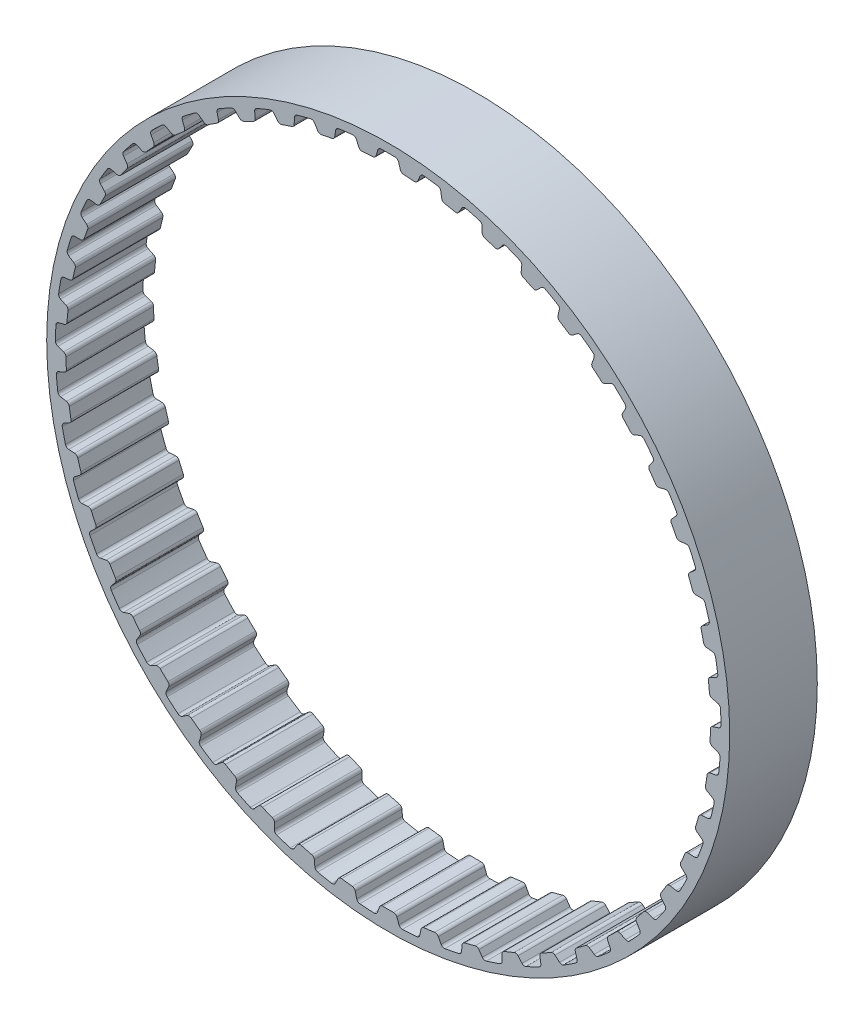
SolidWorks part; units mm, degrees
ref_plane "Front Plane" through (0, 0, 0) normal (0, 0, 1) x (1, 0, 0)
ref_plane "Top Plane" through (0, 0, 0) normal (0, 1, 0) x (1, 0, 0)
ref_plane "Right Plane" through (0, 0, 0) normal (1, 0, 0) x (0, 0, -1)
sketch "Sketch1" plane through (0, 0, 0) normal (0, 0, 1) x (1, 0, 0)
  line L0 (0, 0) -> (-2.3573, 36.7174) construction
  line L1 (0, 0) -> (2.3573, 36.7174) construction
  line L2 (2.3573, 36.7174) -> (-2.3573, 36.7174) construction
  line L3 (2.3573, 36.7174) -> (-2.3573, 36.7174) construction
  circle A0 centre (0, 0) radius 38.993
  circle A1 centre (0, 0) radius 36.793
  circle A2 centre (0, 0) radius 37.993 construction
  dimension "OD" = 77.986
  dimension "Angle Distance" = 7.347
  dimension "hs" = 2.2
  dimension "ht" = 1.2
extrude "Boss-Extrude1" add sketch "Sketch1" along normal mid plane 10
sketch "Sketch2" plane through (0, 0, 0) normal (0, 0, 1) x (1, 0, 0)
  line L1 (0, 38.993) -> (0, 0) construction
  line L2 (-2.5, 37.3759) -> (2.5, 37.3759) construction
  line L4 (-1.4598, 36.775) -> (-3.2549, 36.6598)
  line L5 (-1.4598, 36.775) -> (-1.1077, 37.9768)
  line L6 (-3.2549, 36.6598) -> (-3.7577, 37.8067)
  line L7 (0, 0) -> (-2.3573, 36.7174) construction
  line L8 (-1.1077, 37.9768) -> (-3.7577, 37.8067) construction
  line L9 (1.1077, 37.9768) -> (3.7577, 37.8067) construction
  line L10 (3.2549, 36.6598) -> (3.7577, 37.8067)
  line L11 (1.4598, 36.775) -> (1.1077, 37.9768)
  line L12 (1.4598, 36.775) -> (3.2549, 36.6598)
  line L13 (0, 0) -> (14.922, 36.0248) construction
  line L14 (-2.5, 37.3759) -> (-7.4555, 36.71) construction
  line L15 (-4.9777, 37.043) -> (0, 0) construction
  line L16 (-7.4555, 36.71) -> (-7.3228, 36.0569) construction
  circle A0 centre (0, 0) radius 37.993 construction
  circle A1 centre (0, 0) radius 37.993
  circle A2 centre (0, 0) radius 37.3759 construction
  circle A4 centre (0, 0) radius 38.993 construction
  circle A5 centre (0, 0) radius 36.793 construction
  point P16 (-1.2838, 37.3759)
  point P20 (0, 37.3759)
  dimension "D1" = 22.5
  dimension "bt" = 2.65
  dimension "b" = 40
  dimension "Pitch" = 5
sketch "Sketch3" plane through (0, 0, 0) normal (0, 0, 1) x (1, 0, 0)
  line L0 (-1.7474, 36.7515) -> (1.7474, 36.7515)
  line L2 (-1.4598, 36.775) -> (-1.1077, 37.9768) construction
  line L3 (1.4598, 36.775) -> (1.1077, 37.9768) construction
  line L5 (-1.3826, 37.0386) -> (-1.1898, 37.6968)
  line L7 (1.3826, 37.0386) -> (1.1898, 37.6968)
  arc A0 (1.3826, 37.0386) -> (1.7474, 36.7515) centre (1.7664, 37.151) ccw
  circle A1 centre (0, 0) radius 37.993 construction
  arc A2 (0.8145, 37.9843) -> (-0.8145, 37.9843) centre (0, 0) ccw
  arc A3 (-1.3826, 37.0386) -> (-1.7474, 36.7515) centre (-1.7664, 37.151) cw
  arc A4 (1.1898, 37.6968) -> (0.8145, 37.9843) centre (0.8059, 37.5844) ccw
  arc A5 (-1.1898, 37.6968) -> (-0.8145, 37.9843) centre (-0.8059, 37.5844) cw
  circle A6 centre (0, 0) radius 36.793 construction
  arc A7 (-1.7474, 36.7515) -> (1.7474, 36.7515) centre (0, 0) ccw construction
  dimension "ra" = 0.4
  dimension "rr" = 0.4
extrude "Cut-Extrude1" cut sketch "Sketch3" against normal mid plane 10
pattern_circular "CirPattern1" count 49 over 360 about axis through (0, 0, 0) along (0, 0, 1) of "Cut-Extrude1"
equation "\"D1@Cut-Extrude1\" = \"Width@Boss-Extrude1\""
